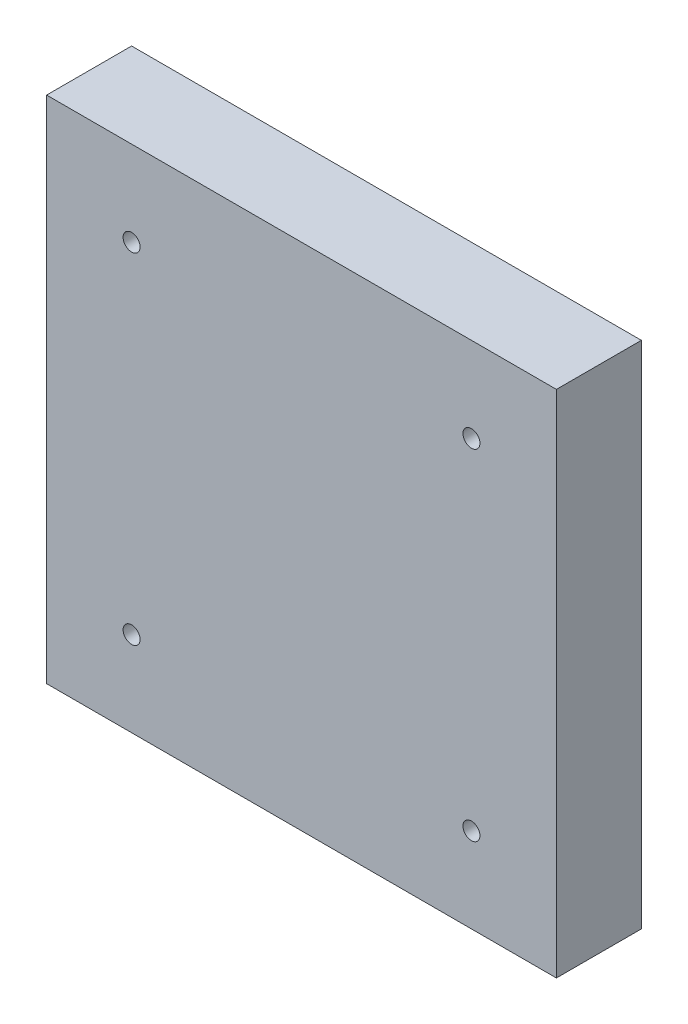
SolidWorks part; units mm, degrees
ref_plane "Front Plane" through (0, 0, 0) normal (0, 0, 1) x (1, 0, 0)
ref_plane "Top Plane" through (0, 0, 0) normal (0, 1, 0) x (1, 0, 0)
ref_plane "Right Plane" through (0, 0, 0) normal (1, 0, 0) x (0, 0, -1)
sketch "Sketch1" plane through (0, 0, 0) normal (0, 0, 1) x (1, 0, 0)
  line L0 (0, 0) -> (0, 76.2)
  line L1 (0, 76.2) -> (76.2, 76.2)
  line L2 (76.2, 76.2) -> (76.2, 0)
  line L3 (76.2, 0) -> (0, 0)
  line L4 (0, 38.1) -> (12.7, 38.1) construction
  line L5 (38.1, 76.2) -> (38.1, 63.5) construction
  line L6 (76.2, 38.1) -> (63.5, 38.1) construction
  line L7 (38.1, 0) -> (38.1, 12.7) construction
  circle A0 centre (12.7, 12.7) radius 1.27
  circle A1 centre (12.7, 63.5) radius 1.27
  circle A2 centre (63.5, 63.5) radius 1.27
  circle A3 centre (63.5, 12.7) radius 1.27
  dimension "D7" = 2.54
  dimension "D1" = 76.2
  dimension "D2" = 76.2
  dimension "D3" = 12.7
  dimension "D4" = 12.7
  dimension "D5" = 12.7
  dimension "D6" = 12.7
extrude "Boss-Extrude1" add sketch "Sketch1" along normal blind 12.7
